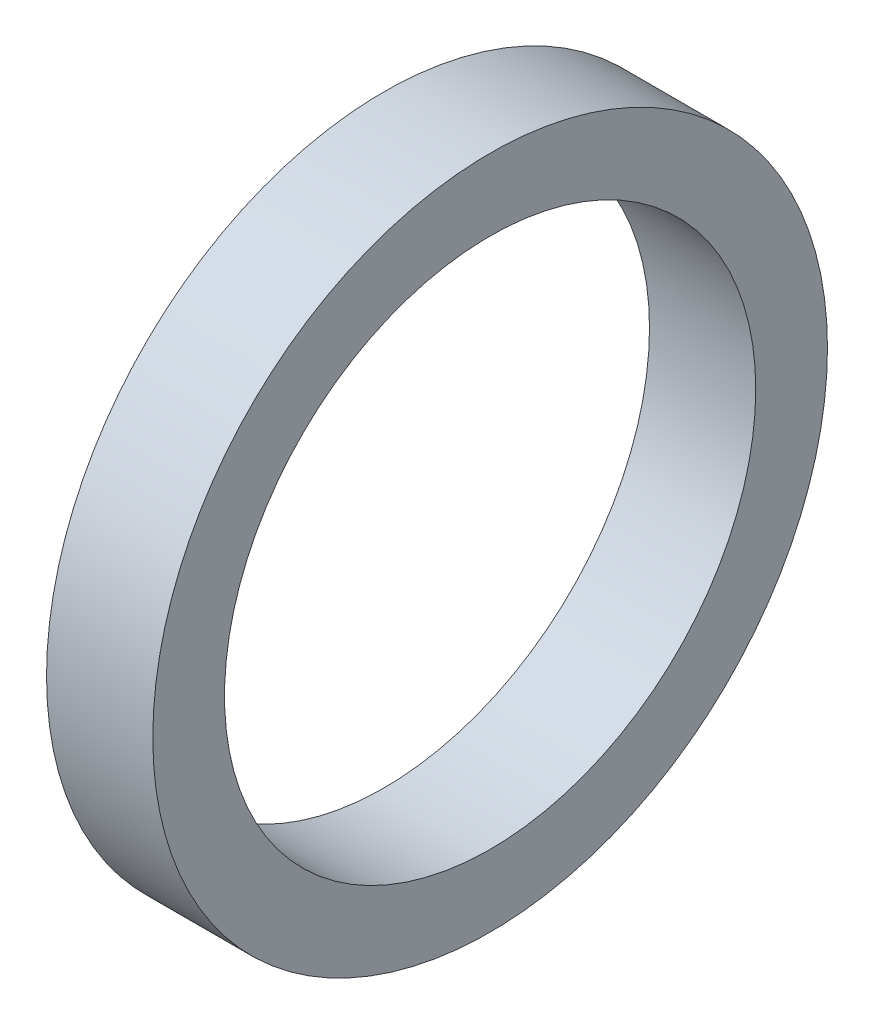
SolidWorks part; units mm, degrees
ref_plane "Front Plane" through (0, 0, 0) normal (0, 0, 1) x (1, 0, 0)
ref_plane "Top Plane" through (0, 0, 0) normal (0, 1, 0) x (1, 0, 0)
ref_plane "Right Plane" through (0, 0, 0) normal (1, 0, 0) x (0, 0, -1)
sketch "Sketch1" plane through (0, 0, 0) normal (1, 0, 0) x (0, 0, -1)
  circle A0 centre (0, 0) radius 15
  circle A1 centre (0, 0) radius 19.05
  dimension "D1" = 30
  dimension "D2" = 38.1
extrude "Boss-Extrude1" add sketch "Sketch1" along normal blind 6
